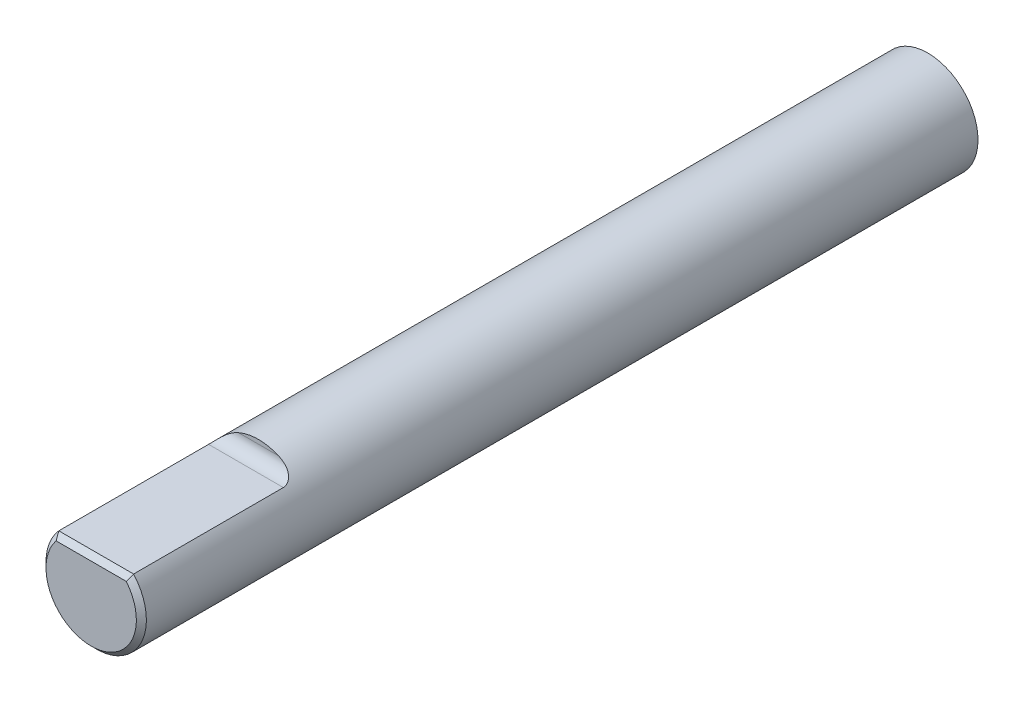
SolidWorks part; units mm, degrees
ref_plane "Front Plane" through (0, 0, 0) normal (0, 0, 1) x (1, 0, 0)
ref_plane "Top Plane" through (0, 0, 0) normal (0, 1, 0) x (1, 0, 0)
ref_plane "Right Plane" through (0, 0, 0) normal (1, 0, 0) x (0, 0, -1)
sketch "Sketch1" plane through (0, 0, 0) normal (0, 0, 1) x (1, 0, 0)
  line L0 (-2.35, 1.8648) -> (2.35, 1.8648) construction
  circle A0 centre (0, 0) radius 3
  dimension "D1" = 6
  dimension "D2" = 4.7
extrude "Boss-Extrude1" add sketch "Sketch1" along normal blind 50 contours L0 A0
sketch "Sketch2" plane through (0, 0, 50) normal (0, 0, 1) x (1, 0, 0)
  line L1 (-2.235, 2.0012) -> (2.235, 2.0012)
  line L2 (-2.235, 2.0012) -> (-2.235, 7.0012)
  line L3 (-2.235, 7.0012) -> (2.235, 7.0012)
  line L4 (2.235, 2.0012) -> (2.235, 7.0012)
  circle A0 centre (0, 0) radius 3 construction
  dimension "D1" = 4.47
  dimension "D2" = 5
extrude "Cut-Extrude2" cut sketch "Sketch2" against normal blind 10
chamfer "Chamfer1" distance 0.3 angle 45 2 edges at (0, -3, 50) (0, 2.0012, 50)
fillet "Fillet1" radius 0.75 1 edges at (0, 2.0012, 40)
